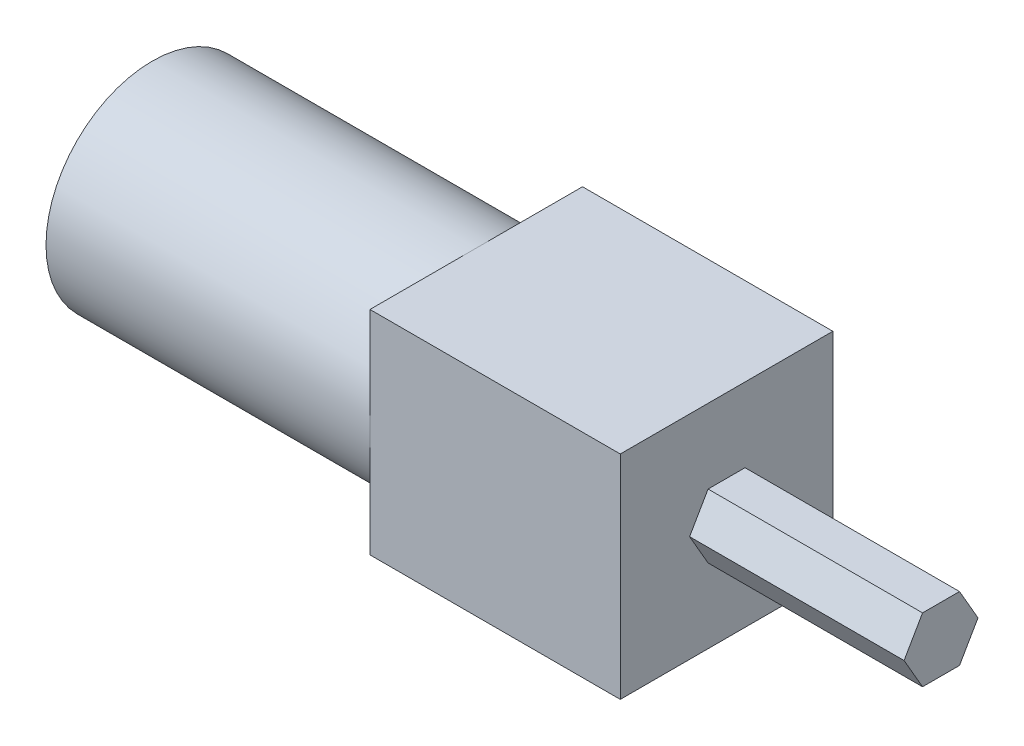
SolidWorks part; units mm, degrees
ref_plane "Front Plane" through (0, 0, 0) normal (0, 0, 1) x (1, 0, 0)
ref_plane "Top Plane" through (0, 0, 0) normal (0, 1, 0) x (1, 0, 0)
ref_plane "Right Plane" through (0, 0, 0) normal (1, 0, 0) x (0, 0, -1)
sketch "Sketch1" plane through (0, 0, 0) normal (1, 0, 0) x (0, 0, -1)
  circle A0 centre (0, 0) radius 21.082
  dimension "D1" = 42.164
extrude "Boss-Extrude1" add sketch "Sketch1" along normal blind 64.262
sketch "Sketch2" plane through (64.262, 0, 0) normal (1, 0, 0) x (0, 0, -1)
  line L1 (-21.082, -21.082) -> (21.082, -21.082)
  line L2 (-21.082, -21.082) -> (-21.082, 21.082)
  line L3 (-21.082, 21.082) -> (21.082, 21.082)
  line L4 (21.082, -21.082) -> (21.082, 21.082)
  line L5 (-21.082, -21.082) -> (21.082, 21.082) construction
  line L6 (-21.082, 21.082) -> (21.082, -21.082) construction
  point P0 (0, 0)
  dimension "D1" = 42.164
  dimension "D2" = 42.164
extrude "Boss-Extrude2" add sketch "Sketch2" along normal blind 49.657
sketch "Sketch3" plane through (113.919, 0, 0) normal (1, 0, 0) x (0, 0, -1)
  line L1 (7.3323, 0) -> (3.6662, 6.35)
  line L2 (3.6662, 6.35) -> (-3.6662, 6.35)
  line L3 (-3.6662, 6.35) -> (-7.3323, 0)
  line L4 (-7.3323, 0) -> (-3.6662, -6.35)
  line L5 (-3.6662, -6.35) -> (3.6662, -6.35)
  line L6 (3.6662, -6.35) -> (7.3323, 0)
  circle A0 centre (0, 0) radius 6.35 construction
  dimension "D1" = 12.7
  dimension "D2" = 6.35
extrude "Boss-Extrude3" add sketch "Sketch3" along normal blind 42.545
